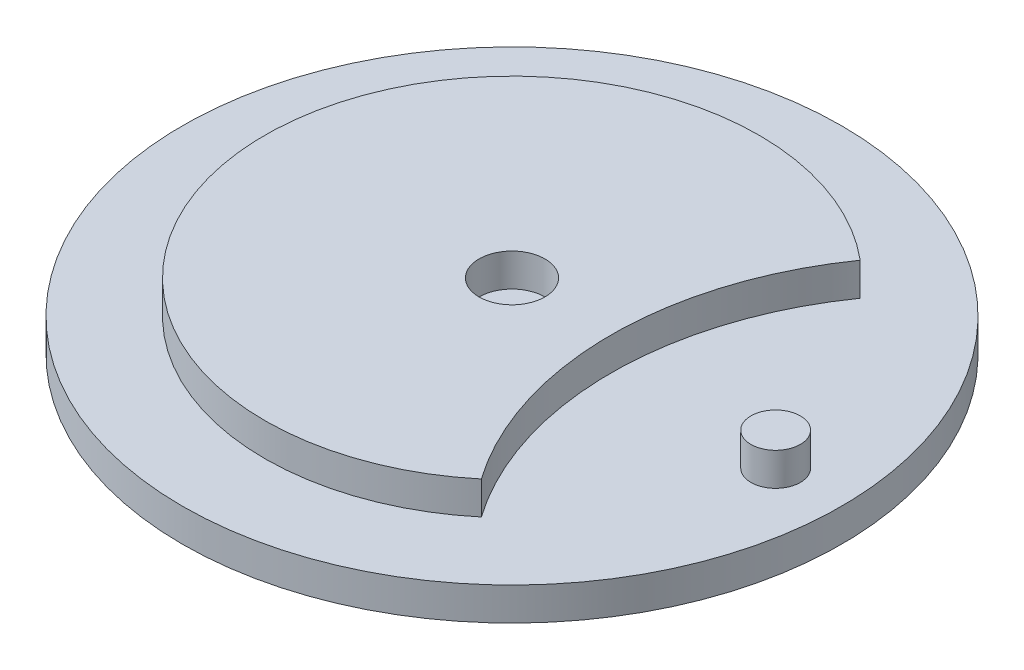
SolidWorks part; units mm, degrees
ref_plane "Front Plane" through (0, 0, 0) normal (0, 0, 1) x (1, 0, 0)
ref_plane "Top Plane" through (0, 0, 0) normal (0, 1, 0) x (1, 0, 0)
ref_plane "Right Plane" through (0, 0, 0) normal (1, 0, 0) x (0, 0, -1)
sketch "Sketch1" plane through (0, 0, 0) normal (0, 1, 0) x (1, 0, 0)
  arc A0 (48.1731, 57.4835) -> (48.1731, -57.4835) centre (0, 0) ccw
  arc A1 (48.1731, 57.4835) -> (48.1731, -57.4835) centre (130, 0) ccw
  circle A2 centre (0, 0) radius 10
  dimension "D1" = 150
  dimension "D2" = 200
  dimension "D4" = 20
  dimension "D3" = 130
extrude "Boss-Extrude1" add sketch "Sketch1" along normal blind 10
sketch "Sketch2" plane through (0, 0, 0) normal (0, -1, 0) x (1, 0, 0)
  circle A0 centre (0, 0) radius 100
  dimension "D1" = 200
extrude "Boss-Extrude2" add sketch "Sketch2" along normal blind 10
sketch "Sketch3" plane through (0, 0, 0) normal (0, 1, 0) x (1, 0, 0)
  circle A0 centre (80, 0) radius 7.5
  dimension "D1" = 15
  dimension "D2" = 80
extrude "Boss-Extrude3" add sketch "Sketch3" along normal blind 10
